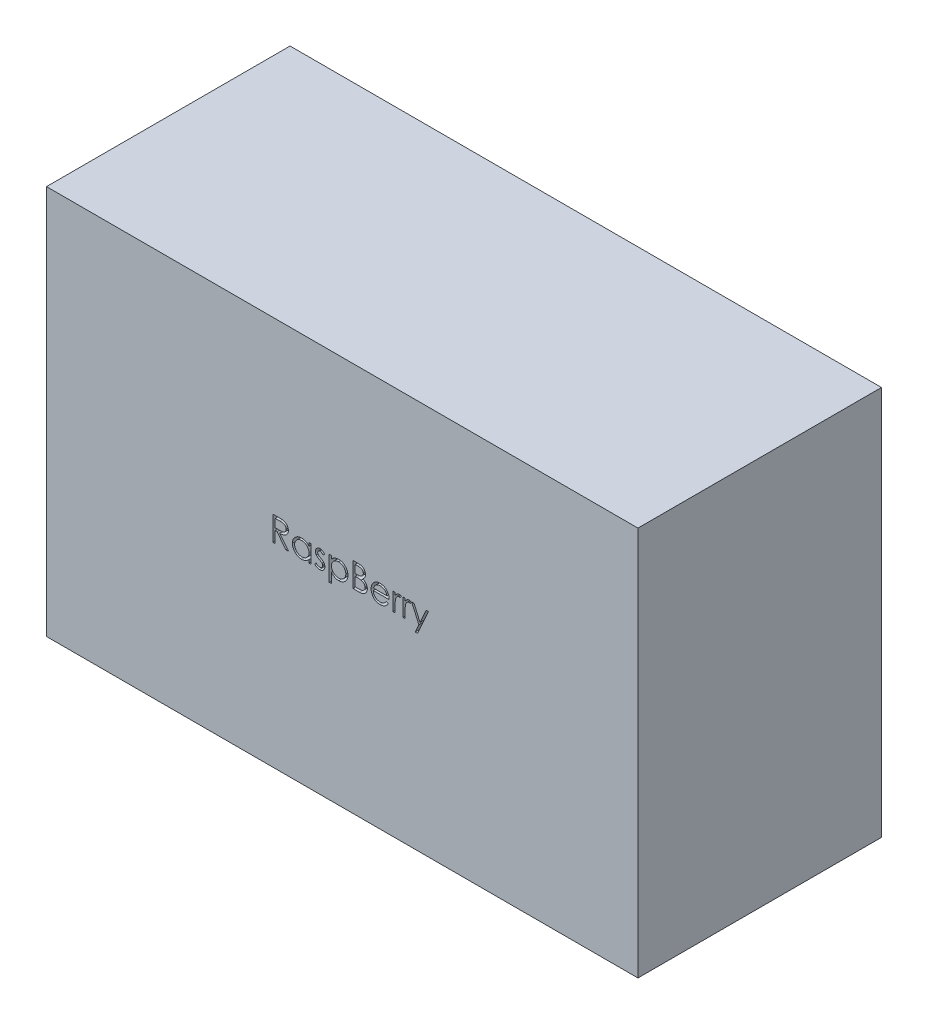
SolidWorks part; units mm, degrees
ref_plane "Alzado" through (0, 0, 0) normal (0, 0, 1) x (1, 0, 0)
ref_plane "Planta" through (0, 0, 0) normal (0, 1, 0) x (1, 0, 0)
ref_plane "Vista lateral" through (0, 0, 0) normal (1, 0, 0) x (0, 0, -1)
sketch "Croquis1" plane through (0, 0, 0) normal (0, 0, 1) x (1, 0, 0)
  line L0 (-24.9075, 0) -> (26.9635, 0) construction
  line L1 (-42.5, -28) -> (42.5, -28)
  line L2 (-42.5, -28) -> (-42.5, 28)
  line L3 (-42.5, 28) -> (42.5, 28)
  line L4 (42.5, -28) -> (42.5, 28)
  line L5 (-42.5, -28) -> (42.5, 28) construction
  line L6 (-42.5, 28) -> (42.5, -28) construction
  line L7 (0, 21.9023) -> (0, -19.2403) construction
  text T0 "RaspBerry"
  point P0 (0, 0)
  dimension "D1" = 85
  dimension "D2" = 56
extrude "Saliente-Extruir2" add sketch "Croquis1" along normal mid plane 35 contours L1 L4 L3 L2
sketch "Croquis3" plane through (0, 0, 0) normal (0, 0, 1) x (1, 0, 0)
  line L0 (-24.9075, 0) -> (26.9635, 0) construction
  line L7 (0, 21.9023) -> (0, -19.2403) construction
  text T0 "RaspBerry"
  point P0 (0, 0)
  point P1 (0, 10.7003)
  point P2 (9.6128, -0.5907)
  point P3 (0, 0)
  point P4 (18.0614, -0.8276)
  point P12 (9.4549, -5.0914)
  point P13 (7.5599, -5.2493)
  dimension "D1" = 7.5599
  dimension "D2" = 5.2493
extrude "Cortar-Extruir1" cut sketch "Croquis3" against normal blind 55 and the other way blind 35
